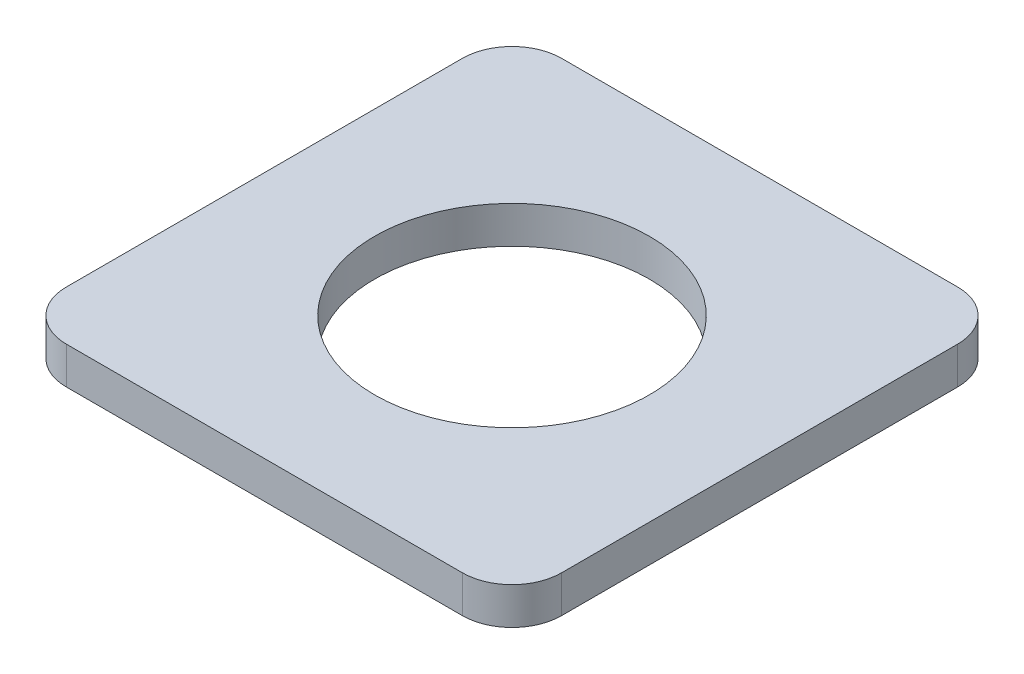
SolidWorks part; units mm, degrees
ref_plane "前视基准面" through (0, 0, 0) normal (0, 0, 1) x (1, 0, 0)
ref_plane "上视基准面" through (0, 0, 0) normal (0, 1, 0) x (1, 0, 0)
ref_plane "右视基准面" through (0, 0, 0) normal (1, 0, 0) x (0, 0, -1)
sketch "草图1" plane through (0, 0, 0) normal (0, 1, 0) x (1, 0, 0)
  line L5 (-16, -20) -> (16, -20)
  line L6 (-20, -16) -> (-20, 16)
  line L11 (-16, 20) -> (16, 20)
  line L12 (20, -16) -> (20, 16)
  line L13 (-20, -20) -> (20, 20) construction
  line L14 (-20, 20) -> (20, -20) construction
  circle A8 centre (0, 0) radius 11.1
  arc A10 (-16, -20) -> (-20, -16) centre (-16, -16) cw
  arc A11 (16, -20) -> (20, -16) centre (16, -16) ccw
  arc A12 (16, 20) -> (20, 16) centre (16, 16) cw
  arc A13 (-20, 16) -> (-16, 20) centre (-16, 16) cw
  point P0 (0, 0)
  point P5 (0, 0)
  point P21 (0, 0)
  dimension "D6" = 22.2
  dimension "D1" = 4
extrude "凸台-拉伸1" add sketch "草图1" along normal blind 3
